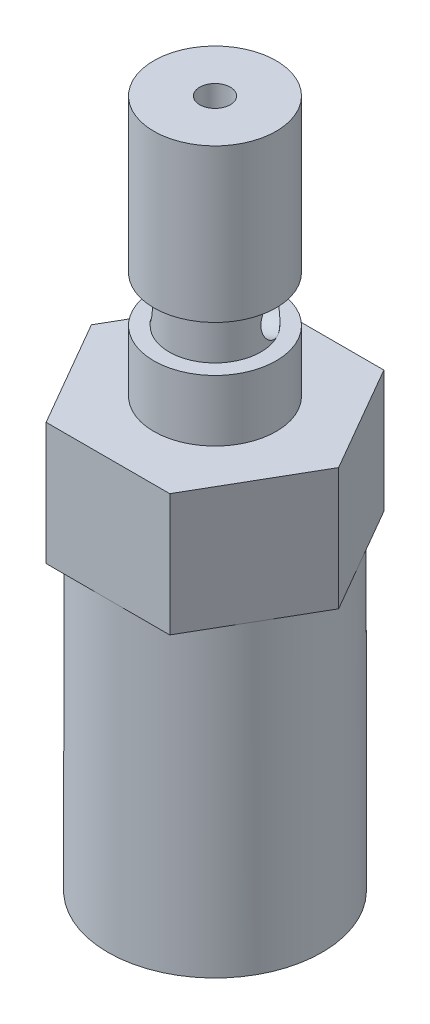
SolidWorks part; units mm, degrees
material "3003 Alloy"
ref_plane "Front" through (0, 0, 0) normal (0, 0, 1) x (1, 0, 0)
ref_plane "Top" through (0, 0, 0) normal (0, 1, 0) x (1, 0, 0)
ref_plane "Right" through (0, 0, 0) normal (1, 0, 0) x (0, 0, -1)
sketch "Sketch1" plane through (0, 0, 0) normal (0, 1, 0) x (1, 0, 0)
  circle A0 centre (0, 0) radius 3.5
extrude "Boss-Extrude1" add sketch "Sketch1" along normal blind 10
sketch "Sketch2" plane through (0, 10, 0) normal (0, 1, 0) x (1, 0, 0)
  line L1 (2.0207, 3.5) -> (-2.0207, 3.5)
  line L2 (-2.0207, 3.5) -> (-4.0415, 0)
  line L3 (-4.0415, 0) -> (-2.0207, -3.5)
  line L4 (-2.0207, -3.5) -> (2.0207, -3.5)
  line L5 (2.0207, -3.5) -> (4.0415, 0)
  line L6 (4.0415, 0) -> (2.0207, 3.5)
  circle A0 centre (0, 0) radius 3.5 construction
extrude "Boss-Extrude2" add sketch "Sketch2" along normal blind 4
sketch "Sketch3" plane through (0, 14, 0) normal (0, 1, 0) x (1, 0, 0)
  circle A0 centre (0, 0) radius 2
extrude "Boss-Extrude3" add sketch "Sketch3" along normal blind 2
sketch "Sketch4" plane through (0, 16, 0) normal (0, 1, 0) x (1, 0, 0)
  circle A0 centre (0, 0) radius 1.5
extrude "Boss-Extrude4" add sketch "Sketch4" along normal blind 1.5
sketch "Sketch5" plane through (0, 17.5, 0) normal (0, 1, 0) x (1, 0, 0)
  circle A0 centre (0, 0) radius 2
extrude "Boss-Extrude5" add sketch "Sketch5" along normal blind 5
cosmetic thread "Cosmetic Thread1" parameters "D1"=4, "D2"=3.22
ref_plane "Plane1" through (-1.299, 0, 0.75) normal (-0.866, 0, 0.5) x (0.5, 0, 0.866)
sketch "Sketch6" plane through (-1.299, 0, 0.75) normal (-0.866, 0, 0.5) x (0.5, 0, 0.866)
  circle A0 centre (0, 16.75) radius 0.75
extrude "Cut-Extrude1" cut sketch "Sketch6" against normal blind 5
sketch "Sketch7" plane through (0, 0, 0) normal (0, -1, 0) x (1, 0, 0)
  circle A0 centre (0, 0) radius 2.5
extrude "Cut-Extrude2" cut sketch "Sketch7" against normal blind 8
sketch "Sketch8" plane through (0, 8, 0) normal (0, -1, 0) x (1, 0, 0)
  circle A0 centre (0, 0) radius 1.5
  dimension "D1" = 3
extrude "Cut-Extrude4" cut sketch "Sketch8" against normal blind 5
cosmetic thread "Cosmetic Thread2" parameters "D2"=4
sketch "Sketch9" plane through (0, 13, 0) normal (0, -1, 0) x (1, 0, 0)
  circle A0 centre (0, 0) radius 0.5
extrude "Cut-Extrude5" cut sketch "Sketch9" against normal through all
